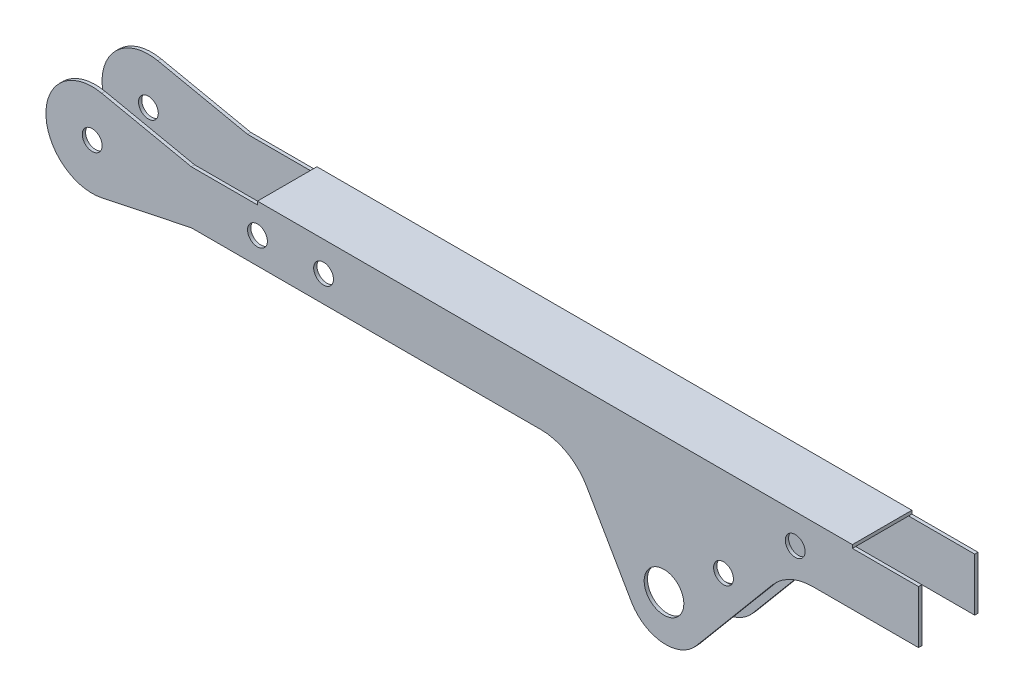
SolidWorks part; units mm, degrees
material "7075-T6，板材(SS)"
ref_plane "前视基准面" through (0, 0, 0) normal (0, 0, 1) x (1, 0, 0)
ref_plane "上视基准面" through (0, 0, 0) normal (0, 1, 0) x (1, 0, 0)
ref_plane "右视基准面" through (0, 0, 0) normal (1, 0, 0) x (0, 0, -1)
sketch "草图1" plane through (0, 0, 0) normal (0, 0, 1) x (1, 0, 0)
  line L0 (-28.9376, 11.8639) -> (81.0624, 11.8639)
  line L1 (-28.9376, 3.8639) -> (28.5624, 3.8639)
  line L2 (-49.4416, 7.8639) -> (82.0027, 7.8639) construction
  line L3 (-28.9376, 11.8639) -> (-42.4977, 14.7142)
  line L4 (-28.9376, 3.8639) -> (-42.4977, 1.0136)
  line L5 (28.5624, 3.8639) -> (41.9222, -19.276)
  line L6 (41.9222, -19.276) -> (61.3388, 3.8639)
  line L7 (81.0624, 11.8639) -> (81.0624, 3.8639)
  line L8 (61.3388, 3.8639) -> (81.0624, 3.8639)
  arc A0 (-42.4977, 14.7142) -> (-42.4977, 1.0136) centre (-43.9376, 7.8639) ccw
  circle A1 centre (-43.9376, 7.8639) radius 1.5
  circle A2 centre (42.5624, -8.1361) radius 3
  circle A3 centre (51.5624, -1.1361) radius 1.5
  circle A4 centre (-18.9376, 7.8639) radius 1.5
  circle A5 centre (-8.9376, 7.8639) radius 1.5
  circle A6 centre (62.4094, 7.8639) radius 1.5
  dimension "D1" = 3
  dimension "D2" = 14
  dimension "D12" = 6
  dimension "D14" = 3
  dimension "D20" = 3
  dimension "D21" = 3
  dimension "D22" = 3
  dimension "D3" = 110
  dimension "D4" = 14
  dimension "D5" = 8
  dimension "D6" = 15
  dimension "D7" = 15
  dimension "D8" = 4
  dimension "D9" = 86.5
  dimension "D10" = 60
  dimension "D11" = 50
  dimension "D15" = 5
  dimension "D16" = 23
  dimension "D17" = 12
  dimension "D18" = 25
  dimension "D19" = 35
extrude "凸台-拉伸1" add sketch "草图1" along normal blind 0.5
ref_plane "基准面1" through (0, 0, -8) normal (0, 0, 1) x (1, 0, 0)
sketch "草图3" plane through (0, 0, -8) normal (0, 0, 1) x (1, 0, 0)
  line L8 (41.9222, -19.276) -> (61.3388, 3.8639)
  line L9 (61.3388, 3.8639) -> (81.0624, 3.8639)
  line L10 (81.0624, 3.8639) -> (81.0624, 11.8639)
  line L11 (81.0624, 11.8639) -> (-28.9376, 11.8639)
  line L12 (-28.9376, 11.8639) -> (-42.4977, 14.7142)
  line L13 (-42.4977, 1.0136) -> (-28.9376, 3.8639)
  line L14 (-28.9376, 3.8639) -> (28.5624, 3.8639)
  line L15 (28.5624, 3.8639) -> (41.9222, -19.276)
  line L16 (41.9222, -19.276) -> (61.3388, 3.8639)
  line L17 (61.3388, 3.8639) -> (81.0624, 3.8639)
  line L18 (81.0624, 3.8639) -> (81.0624, 11.8639)
  line L19 (81.0624, 11.8639) -> (-28.9376, 11.8639)
  line L20 (-28.9376, 11.8639) -> (-42.4977, 14.7142)
  line L21 (-42.4977, 1.0136) -> (-28.9376, 3.8639)
  line L22 (-28.9376, 3.8639) -> (28.5624, 3.8639)
  line L23 (28.5624, 3.8639) -> (41.9222, -19.276)
  circle A1 centre (51.5624, -1.1361) radius 1.5
  circle A2 centre (51.5624, -1.1361) radius 1.5
  circle A3 centre (42.5624, -8.1361) radius 3
  circle A4 centre (42.5624, -8.1361) radius 3
  circle A5 centre (-43.9376, 7.8639) radius 1.5
  circle A6 centre (-43.9376, 7.8639) radius 1.5
  circle A7 centre (62.4094, 7.8639) radius 1.5
  circle A8 centre (62.4094, 7.8639) radius 1.5
  circle A9 centre (-8.9376, 7.8639) radius 1.5
  circle A10 centre (-8.9376, 7.8639) radius 1.5
  circle A11 centre (-18.9376, 7.8639) radius 1.5
  circle A12 centre (-18.9376, 7.8639) radius 1.5
  arc A13 (-42.4977, 14.7142) -> (-42.4977, 1.0136) centre (-43.9376, 7.8639) ccw
  arc A14 (-42.4977, 14.7142) -> (-42.4977, 1.0136) centre (-43.9376, 7.8639) ccw
  dimension "D1" = 0
  dimension "D2" = 0
  dimension "D3" = 0
  dimension "D4" = 0
  dimension "D5" = 0
  dimension "D6" = 0
  dimension "D7" = 0
extrude "凸台-拉伸2" add sketch "草图3" against normal blind 0.5 separate body
ref_plane "基准面3" through (0, 11.8639, 0) normal (0, 1, 0) x (1, 0, 0)
sketch "草图4" plane through (0, 11.8639, 0) normal (0, 1, 0) x (1, 0, 0)
  line L0 (71.0624, 8.5) -> (71.0624, -0.5)
  line L1 (71.0624, -0.5) -> (-18.9376, -0.5)
  line L2 (81.0624, -0.5) -> (-28.9376, -0.5) construction
  line L3 (-18.9376, -0.5) -> (-18.9376, 8.5)
  line L4 (81.0624, 8.5) -> (-28.9376, 8.5) construction
  line L5 (-18.9376, 8.5) -> (71.0624, 8.5)
  line L6 (-43.9376, 8.5) -> (-43.9376, 8) construction
  line L8 (81.0624, 13.7104) -> (81.0624, -2.5495) construction
  dimension "D1" = 25
  dimension "D2" = 10
extrude "凸台-拉伸3" add sketch "草图4" along normal blind 0.5
fillet "圆角1" radius 8 4 edges at (28.5624, 3.8639, 0.25) (28.5624, 3.8639, -8.25) (61.3388, 3.8639, 0.25) (61.3388, 3.8639, -8.25)
fillet "圆角2" radius 6 2 edges at (41.9222, -19.276, -8.25) (41.9222, -19.276, 0.25)
